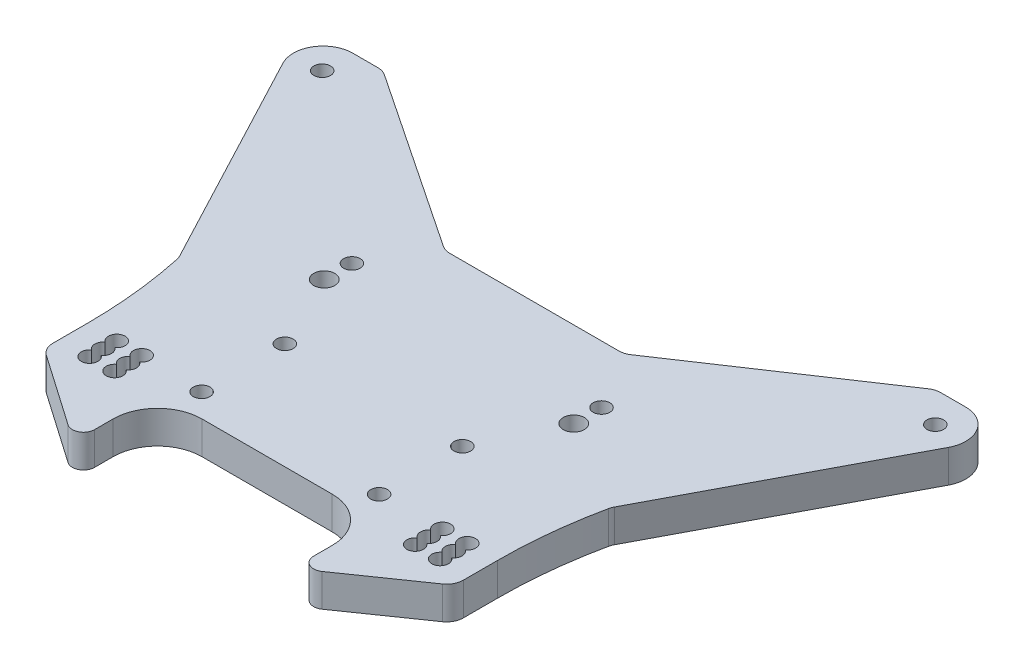
SolidWorks part; units mm, degrees
material "Liga 1060"
ref_plane "Plano frontal" through (0, 0, 0) normal (0, 0, 1) x (1, 0, 0)
ref_plane "Plano superior" through (0, 0, 0) normal (0, 1, 0) x (1, 0, 0)
ref_plane "Plano direito" through (0, 0, 0) normal (1, 0, 0) x (0, 0, -1)
sketch "Esboço1" plane through (0, 0, 0) normal (0, 1, 0) x (1, 0, 0)
  line L0 (0, 88.7468) -> (0, -33.8571) construction
  line L1 (19.75, -23.0638) -> (-19.75, -23.0638)
  line L2 (-19.75, -23.0638) -> (-19.75, -34.4138)
  line L3 (-22.891, -36.0564) -> (-37, -26.2564)
  line L4 (-37, -26.2564) -> (-37, -18.5564)
  line L5 (-39, 0) -> (-60, 39.7995)
  line L6 (-55.2683, 47.6462) -> (-49.8183, 47.6462)
  line L7 (-49.8183, 47.6462) -> (-16.15, 25.1362)
  line L8 (-16.15, 25.1362) -> (16.15, 25.1362)
  line L9 (49.8183, 47.6462) -> (16.15, 25.1362)
  line L10 (55.2683, 47.6462) -> (49.8183, 47.6462)
  line L11 (39, 0) -> (60, 39.7995)
  line L12 (37, -26.2564) -> (37, -18.5564)
  line L13 (22.891, -36.0564) -> (37, -26.2564)
  line L14 (19.75, -23.0638) -> (19.75, -34.4138)
  arc A0 (-19.75, -34.4138) -> (-22.891, -36.0564) centre (-21.75, -34.4138) cw
  arc A1 (-60, 39.7995) -> (-55.2683, 47.6462) centre (-55.2683, 42.2962) cw
  arc A2 (-37, -18.5564) -> (-39, 0) centre (-124.0849, -18.5564) ccw
  arc A3 (37, -18.5564) -> (39, 0) centre (124.0849, -18.5564) cw
  arc A4 (60, 39.7995) -> (55.2683, 47.6462) centre (55.2683, 42.2962) ccw
  arc A5 (19.75, -34.4138) -> (22.891, -36.0564) centre (21.75, -34.4138) ccw
  point P28 (0, 25.1362)
  point P31 (0, -23.0638)
  dimension "D3" = 2
  dimension "D15" = 5.35
  dimension "D1" = 19.75
  dimension "D2" = 11.35
  dimension "D4" = 37
  dimension "D5" = 48.2
  dimension "D6" = 40.5
  dimension "D7" = 9.8
  dimension "D8" = 7.7
  dimension "D9" = 39
  dimension "D12" = 45
  dimension "D13" = 60
  dimension "D14" = 5.45
  dimension "D16" = 16.15
extrude "Ressalto-extrusão1" add sketch "Esboço1" along normal blind 5.9
fillet "Filete1" radius 8 2 edges at (19.75, 2.95, 23.0638) (-19.75, 2.95, 23.0638)
fillet "Filete2" radius 3 8 edges at (-49.8183, 2.95, -47.6462) (-39, 2.95, 0) (-37, 2.95, 26.2564) (37, 2.95, 26.2564) (39, 2.95, 0) (49.8183, 2.95, -47.6462) (16.15, 2.95, -25.1362) (-16.15, 2.95, -25.1362)
sketch "Esboço2" plane through (0, 0, 0) normal (0, -1, 0) x (1, 0, 0)
  line L0 (-52.946, -45.9744) -> (-34.7509, -34.4871)
  line L1 (-39.3954, -27.1306) -> (-57.5905, -38.6179)
  line L3 (-16.9069, -25.6423) -> (-49.0614, -47.1401) construction
  line L5 (0, -86.5939) -> (0, 36.3665) construction
  line L6 (39.3954, -27.1306) -> (57.5905, -38.6179)
  line L7 (52.946, -45.9744) -> (34.7509, -34.4871)
  line L8 (-50.7288, -47.6462) -> (-55.2683, -47.6462) construction
  arc A0 (-57.5905, -38.6179) -> (-52.946, -45.9744) centre (-55.2683, -42.2962) ccw
  arc A1 (-34.7509, -34.4871) -> (-39.3954, -27.1306) centre (-37.0732, -30.8088) ccw
  arc A2 (-60, -39.7995) -> (-55.2683, -47.6462) centre (-55.2683, -42.2962) ccw construction
  arc A3 (57.5905, -38.6179) -> (52.946, -45.9744) centre (55.2683, -42.2962) cw
  arc A4 (34.7509, -34.4871) -> (39.3954, -27.1306) centre (37.0732, -30.8088) cw
  circle A5 centre (-55.2683, -42.1462) radius 1.5
  circle A6 centre (55.2683, -42.1462) radius 1.5
  dimension "D1" = 8.7
  dimension "D2" = 3
  dimension "D4" = 21.5179
  dimension "D3" = 178.5
  dimension "D5" = 5.5
extrude "Corte-extrusão2" cut sketch "Esboço2" against normal blind 2
sketch "Esboço4" plane through (0, 0, 0) normal (0, -1, 0) x (1, 0, 0)
  line L0 (0, -61.34) -> (0, -31.5304) construction
  line L1 (15.2395, -25.1362) -> (-15.2395, -25.1362) construction
  line L2 (-11.75, 23.0638) -> (11.75, 23.0638) construction
  circle A0 centre (-55.2683, -42.1462) radius 1.5
  circle A1 centre (55.2683, -42.1462) radius 1.5
  circle A2 centre (-22.5, -14.7362) radius 1.5
  circle A3 centre (-22.5, -9.7362) radius 1.9
  circle A4 centre (-16, 3.8638) radius 1.5
  circle A5 centre (-16, 18.8638) radius 1.5
  arc A6 (-32.4657, 19.7888) -> (-30.7343, 19.7888) centre (-31.6, 18.5638) ccw
  arc A7 (-30.7343, 22.2388) -> (-32.4657, 22.2388) centre (-31.6, 23.4638) ccw
  arc A8 (-32.4657, 22.2388) -> (-32.4657, 19.7888) centre (-31.6, 21.0138) ccw
  arc A9 (-27.9657, 19.7888) -> (-26.2343, 19.7888) centre (-27.1, 18.5638) ccw
  arc A10 (-26.2343, 22.2388) -> (-27.9657, 22.2388) centre (-27.1, 23.4638) ccw
  arc A11 (-27.9657, 22.2388) -> (-27.9657, 19.7888) centre (-27.1, 21.0138) ccw
  arc A12 (-30.7343, 19.7888) -> (-30.7343, 22.2388) centre (-31.6, 21.0138) ccw
  arc A13 (-26.2343, 19.7888) -> (-26.2343, 22.2388) centre (-27.1, 21.0138) ccw
  arc A14 (26.2343, 19.7888) -> (26.2343, 22.2388) centre (27.1, 21.0138) cw
  arc A15 (30.7343, 19.7888) -> (30.7343, 22.2388) centre (31.6, 21.0138) cw
  arc A16 (27.9657, 22.2388) -> (27.9657, 19.7888) centre (27.1, 21.0138) cw
  arc A17 (26.2343, 22.2388) -> (27.9657, 22.2388) centre (27.1, 23.4638) cw
  arc A18 (27.9657, 19.7888) -> (26.2343, 19.7888) centre (27.1, 18.5638) cw
  arc A19 (32.4657, 22.2388) -> (32.4657, 19.7888) centre (31.6, 21.0138) cw
  arc A20 (30.7343, 22.2388) -> (32.4657, 22.2388) centre (31.6, 23.4638) cw
  arc A21 (32.4657, 19.7888) -> (30.7343, 19.7888) centre (31.6, 18.5638) cw
  circle A22 centre (16, 18.8638) radius 1.5
  circle A23 centre (16, 3.8638) radius 1.5
  circle A24 centre (22.5, -9.7362) radius 1.9
  circle A25 centre (22.5, -14.7362) radius 1.5
  point P21 (0, 0)
  point P37 (0, 0)
  dimension "D1" = 3
  dimension "D2" = 3.8
  dimension "D6" = 3
  dimension "D10" = 3
  dimension "D11" = 3
  dimension "D14" = 4.9
  dimension "D15" = 3
  dimension "D16" = 3
  dimension "D18" = 3
  dimension "D20" = 3
  dimension "D23" = 1.5
  dimension "D3" = 22.5
  dimension "D4" = 10.4
  dimension "D5" = 5
  dimension "D7" = 16
  dimension "D8" = 29
  dimension "D9" = 15
  dimension "D12" = 31.6
  dimension "D13" = 4.5
  dimension "D17" = 2.45
  dimension "D19" = 4.9
  dimension "D21" = 2.45
  dimension "D22" = 4.5
extrude "Corte-extrusão3" cut sketch "Esboço4" against normal through all
